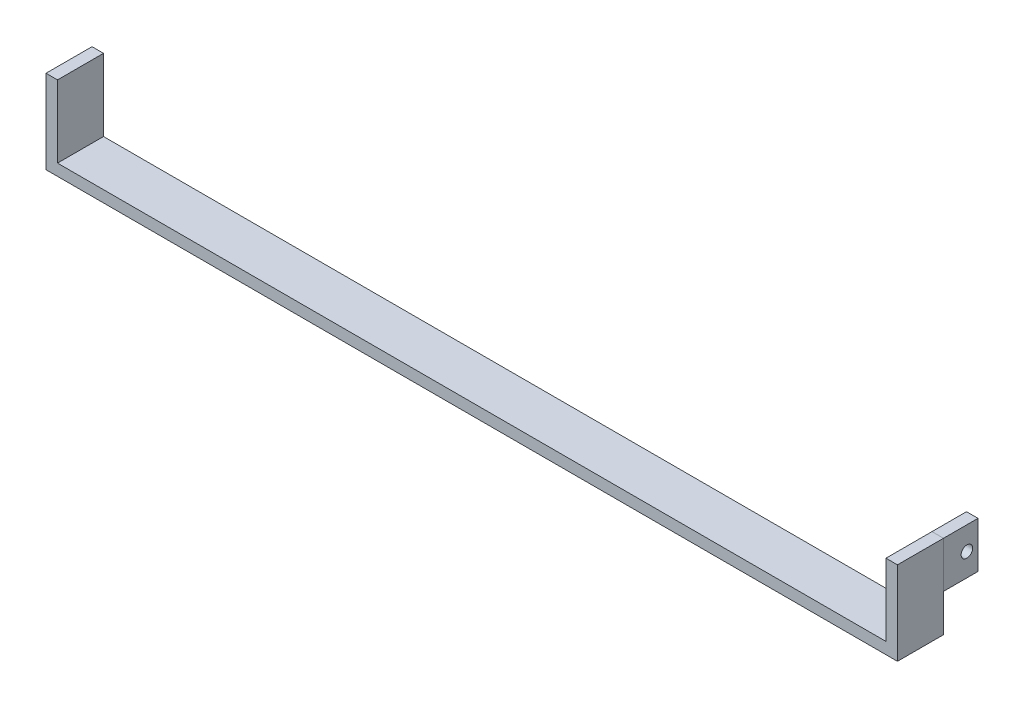
SolidWorks part; units mm, degrees
ref_plane "Front Plane" through (0, 0, 0) normal (0, 0, 1) x (1, 0, 0)
ref_plane "Top Plane" through (0, 0, 0) normal (0, 1, 0) x (1, 0, 0)
ref_plane "Right Plane" through (0, 0, 0) normal (1, 0, 0) x (0, 0, -1)
sketch "Sketch1" plane through (0, 0, 0) normal (0, 1, 0) x (1, 0, 0)
  line L1 (0, 0) -> (370, 0)
  line L2 (0, 0) -> (0, 20)
  line L3 (0, 20) -> (370, 20)
  line L4 (370, 0) -> (370, 20)
  dimension "D1" = 370
  dimension "D2" = 20
extrude "Boss-Extrude1" add sketch "Sketch1" along normal blind 5
sketch "Sketch2" plane through (0, 5, 0) normal (0, 1, 0) x (1, 0, 0)
  line L0 (0, 0) -> (370, 0) construction
  line L1 (0, 20) -> (5, 20)
  line L2 (0, 20) -> (0, 0)
  line L3 (0, 0) -> (5, 0)
  line L4 (5, 20) -> (5, 0)
  line L5 (370, 20) -> (0, 20) construction
  line L6 (365, 20) -> (370, 20)
  line L7 (365, 20) -> (365, 0)
  line L8 (365, 0) -> (370, 0)
  line L9 (370, 20) -> (370, 0)
  dimension "D1" = 5
  dimension "D2" = 5
extrude "Boss-Extrude2" add sketch "Sketch2" along normal blind 31.32
sketch "Sketch3" plane through (0, 0, -20) normal (0, 0, -1) x (-1, 0, 0)
  line L0 (-365, 36.32) -> (-365, 5) construction
  line L1 (-370, 36.32) -> (-365, 36.32)
  line L2 (-370, 36.32) -> (-370, 16.32)
  line L3 (-370, 16.32) -> (-365, 16.32)
  line L4 (-365, 36.32) -> (-365, 16.32)
  dimension "D1" = 20
extrude "Boss-Extrude3" add sketch "Sketch3" along normal blind 15 separate body
sketch "Sketch4" plane through (370, 0, 0) normal (1, 0, 0) x (0, 0, -1)
  line L0 (35, 36.32) -> (20, 36.32) construction
  line L2 (20, 36.32) -> (20, 0) construction
  circle A0 centre (30.17, 26.24) radius 2.5
  dimension "D1" = 5
  dimension "D2" = 10.08
  dimension "D3" = 10.17
extrude "Cut-Extrude1" cut sketch "Sketch4" against normal blind 15
